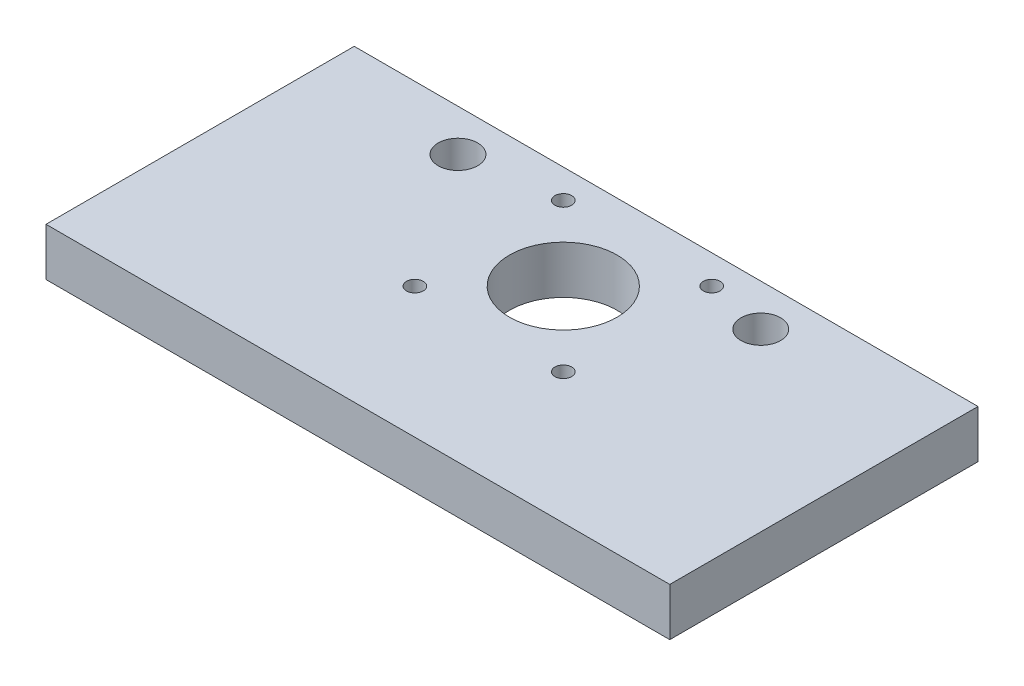
SolidWorks part; units mm, degrees
material "ABS PC"
ref_plane "Спереди" through (0, 0, 0) normal (0, 0, 1) x (1, 0, 0)
ref_plane "Сверху" through (0, 0, 0) normal (0, 1, 0) x (1, 0, 0)
ref_plane "Справа" through (0, 0, 0) normal (1, 0, 0) x (0, 0, -1)
sketch "Sketch1" plane through (0, 0, 0) normal (0, 1, 0) x (1, 0, 0)
  line L0 (49.7185, 58.345) -> (80.7185, 27.345) construction
  line L1 (0, 0) -> (130.309, 0)
  line L2 (0, 0) -> (0, 64.3891)
  line L3 (0, 64.3891) -> (130.309, 64.3891)
  line L4 (130.309, 0) -> (130.309, 64.3891)
  circle A0 centre (49.7185, 58.345) radius 1.75
  circle A1 centre (80.7185, 58.345) radius 1.75
  circle A2 centre (49.7185, 27.345) radius 1.75
  circle A3 centre (80.7185, 27.345) radius 1.75
  circle A4 centre (65.2185, 42.845) radius 11.25
  circle A5 centre (30.3813, 55.6798) radius 4.1318
  circle A6 centre (93.6383, 55.6798) radius 4.1318
  point P15 (65.2185, 42.845)
  dimension "D1" = 31
  dimension "D2" = 31
  dimension "D3" = 31
  dimension "D4" = 3.5
  dimension "D5" = 22.5
extrude "Boss-Extrude1" add sketch "Sketch1" along normal blind 10
